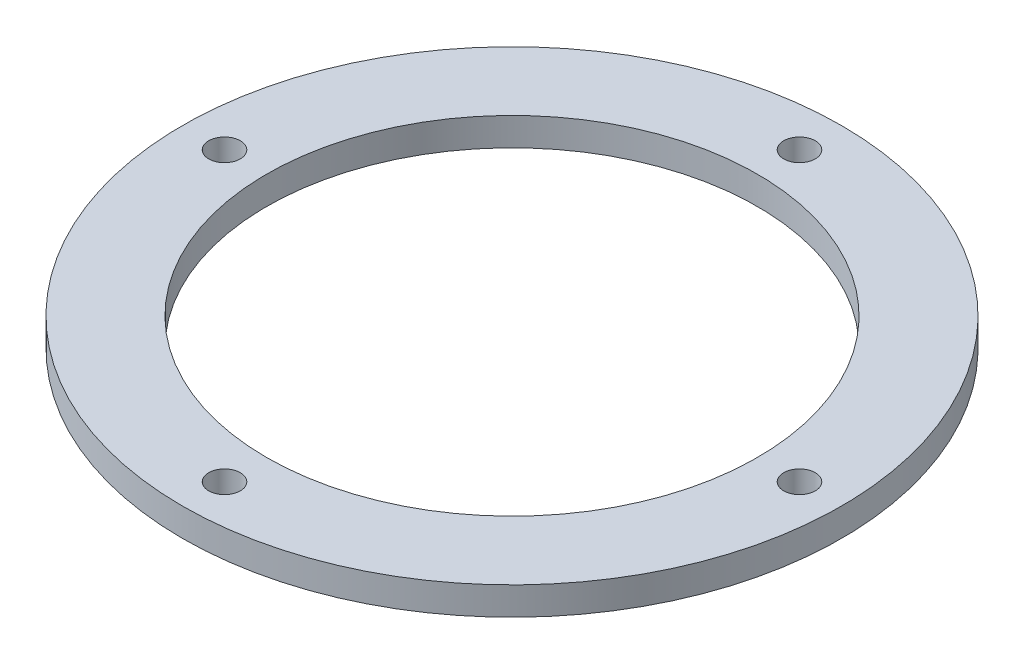
SolidWorks part; units mm, degrees
material "ABS"
ref_plane "Piano frontale" through (0, 0, 0) normal (0, 0, 1) x (1, 0, 0)
ref_plane "Piano superiore" through (0, 0, 0) normal (0, 1, 0) x (1, 0, 0)
ref_plane "Piano destro" through (0, 0, 0) normal (1, 0, 0) x (0, 0, -1)
sketch "Schizzo1" plane through (0, 0, 0) normal (0, 1, 0) x (1, 0, 0)
  circle A0 centre (0, 0) radius 47
  circle A1 centre (0, 0) radius 35
  point P3 (0, 0)
  dimension "D1" = 94
  dimension "D2" = 70
extrude "Estrusione-Estrusione1" add sketch "Schizzo1" along normal blind 4
sketch "Schizzo2" plane through (0, 4, 0) normal (0, 1, 0) x (1, 0, 0)
  line L0 (0, 41) -> (0, -41) construction
  line L1 (-41, 0) -> (41, 0) construction
  circle A0 centre (0, 0) radius 41 construction
  circle A1 centre (0, 41) radius 2.25
  circle A2 centre (41, 0) radius 2.25
  circle A3 centre (0, -41) radius 2.25
  circle A4 centre (-41, 0) radius 2.25
  circle A5 centre (0, 0) radius 35 construction
  dimension "D1" = 4.5
  dimension "D2" = 6
extrude "Taglio-Estrusione1" cut sketch "Schizzo2" against normal blind 4
